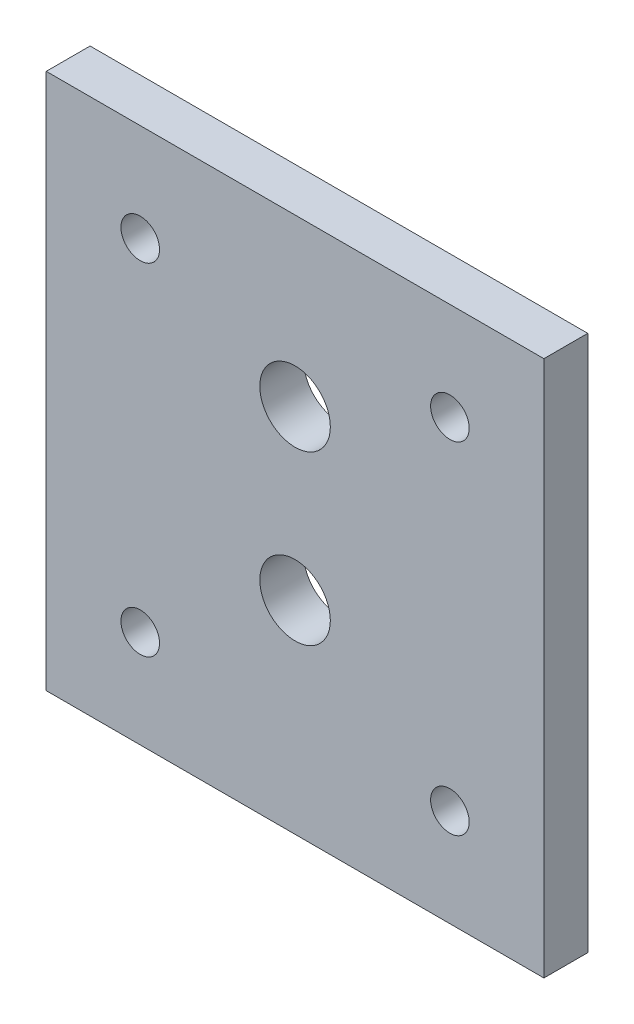
SolidWorks part; units mm, degrees
ref_plane "Front Plane" through (0, 0, 0) normal (0, 0, 1) x (1, 0, 0)
ref_plane "Top Plane" through (0, 0, 0) normal (0, 1, 0) x (1, 0, 0)
ref_plane "Right Plane" through (0, 0, 0) normal (1, 0, 0) x (0, 0, -1)
sketch "Sketch1" plane through (0, 0, 0) normal (0, 0, 1) x (1, 0, 0)
  line L0 (23.5034, -26.6844) -> (45.9189, -26.6844) construction
  line L1 (16.6987, 5.0709) -> (52.7236, 5.0709)
  line L2 (16.6987, 5.0709) -> (16.6987, -33.756)
  line L3 (16.6987, -33.756) -> (52.7236, -33.756)
  line L4 (52.7236, 5.0709) -> (52.7236, -33.756)
  line L5 (34.7111, -6.9374) -> (34.7111, -19.0791) construction
  line L6 (23.5034, -26.6844) -> (23.5034, -33.756) construction
  line L11 (45.9189, -26.6844) -> (45.9189, -2.0006) construction
  line L13 (45.9189, -14.3425) -> (52.7236, -14.3425) construction
  line L14 (34.7111, -19.0791) -> (45.9189, -19.0791) construction
  circle A1 centre (45.9189, -2.0006) radius 1.397
  circle A2 centre (23.5034, -2.0006) radius 1.397
  circle A3 centre (23.5034, -26.6844) radius 1.397
  circle A4 centre (45.9189, -26.6844) radius 1.397
  circle A5 centre (34.7111, -6.9374) radius 2.5527
  circle A6 centre (34.7111, -19.0791) radius 2.5527
extrude "Boss-Extrude1" add sketch "Sketch1" along normal blind 3.175
